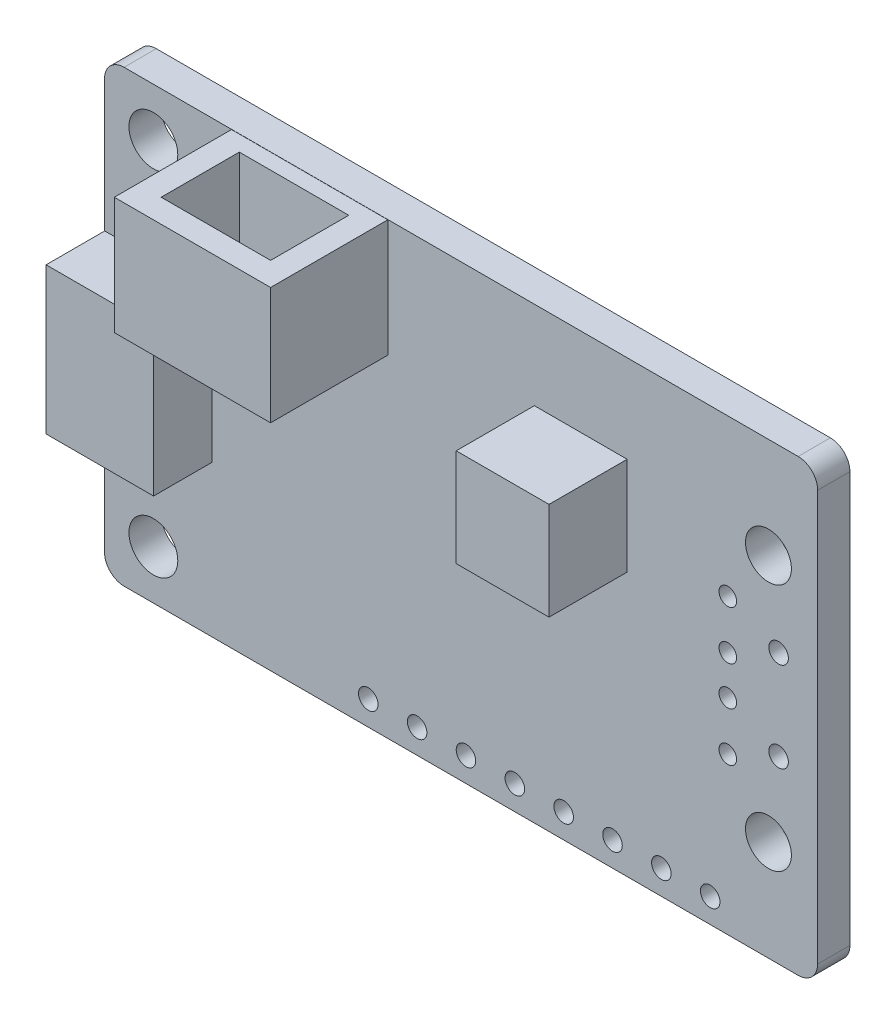
SolidWorks part; units mm, degrees
ref_plane "Front Plane" through (0, 0, 0) normal (0, 0, 1) x (1, 0, 0)
ref_plane "Top Plane" through (0, 0, 0) normal (0, 1, 0) x (1, 0, 0)
ref_plane "Right Plane" through (0, 0, 0) normal (1, 0, 0) x (0, 0, -1)
sketch "Sketch1" plane through (0, 0, 0) normal (0, 0, 1) x (1, 0, 0)
  line L1 (-17.25, -11.5) -> (17.25, -11.5)
  line L2 (-18.25, -10.5) -> (-18.25, 10.5)
  line L3 (-17.25, 11.5) -> (17.25, 11.5)
  line L4 (18.25, -10.5) -> (18.25, 10.5)
  line L5 (-18.25, -11.5) -> (18.25, 11.5) construction
  line L6 (-18.25, 11.5) -> (18.25, -11.5) construction
  arc A0 (-17.25, -11.5) -> (-18.25, -10.5) centre (-17.25, -10.5) cw
  arc A1 (17.25, -11.5) -> (18.25, -10.5) centre (17.25, -10.5) ccw
  arc A2 (17.25, 11.5) -> (18.25, 10.5) centre (17.25, 10.5) cw
  arc A3 (-18.25, 10.5) -> (-17.25, 11.5) centre (-17.25, 10.5) cw
  point P0 (0, 0)
  dimension "D3" = 1
  dimension "D1" = 36.5
  dimension "D2" = 23
extrude "Base" add sketch "Sketch1" along normal blind 1.65
sketch "Sketch2" plane through (0, 0, 1.65) normal (0, 0, 1) x (1, 0, 0)
  line L0 (17.25, 11.5) -> (-17.25, 11.5) construction
  line L1 (-18.25, 10.5) -> (-18.25, -10.5) construction
  circle A0 centre (-15.75, 9) radius 1.25
  dimension "D1" = 2.5
  dimension "D2" = 2.5
  dimension "D3" = 2.5
extrude "Cut-Extrude1" cut sketch "Sketch2" against normal through all
mirror "Mirror1" about plane through (0, 0, 0) normal (0, 1, 0) of "Cut-Extrude1"
sketch "Sketch3" plane through (0, 0, 1.65) normal (0, 0, 1) x (1, 0, 0)
  line L0 (-17.25, -11.5) -> (17.25, -11.5) construction
  line L1 (18.25, -10.5) -> (18.25, 10.5) construction
  circle A0 centre (12.75, -10.25) radius 0.5
  dimension "D1" = 1
  dimension "D2" = 1.25
  dimension "D3" = 5.5
extrude "Cut-Extrude2" cut sketch "Sketch3" against normal through all
pattern_linear "LPattern1" count 8 spacing 2.5 along (-1, 0, 0) of "Cut-Extrude2"
sketch "Sketch4" plane through (0, 0, 1.65) normal (0, 0, 1) x (1, 0, 0)
  line L0 (-17.25, -11.5) -> (17.25, -11.5) construction
  circle A1 centre (15.7309, -6.3475) radius 1.175
  dimension "D1" = 2.35
  dimension "D3" = 5.1525
extrude "Cut-Extrude3" cut sketch "Sketch4" against normal through all
sketch "Sketch9" plane through (0, 0, 1.65) normal (0, 0, 1) x (1, 0, 0)
  line L0 (18.25, -10.5) -> (18.25, 10.5) construction
  line L1 (17.25, 11.5) -> (-17.25, 11.5) construction
  circle A0 centre (13.65, 1) radius 0.45
  circle A1 centre (13.65, 3.5) radius 0.45
  dimension "D1" = 0.9
  dimension "D2" = 0.9
  dimension "D3" = 4.6
  dimension "D4" = 8
  dimension "D5" = 10.5
extrude "Cut-Extrude6" cut sketch "Sketch9" against normal through all
sketch "Sketch10" plane through (0, 0, 1.65) normal (0, 0, 1) x (1, 0, 0)
  line L0 (18.25, -10.5) -> (18.25, 10.5) construction
  line L1 (17.25, 11.5) -> (-17.25, 11.5) construction
  circle A0 centre (16.25, 2.3) radius 0.5
  dimension "D1" = 1
  dimension "D2" = 2
  dimension "D3" = 9.2
extrude "Cut-Extrude7" cut sketch "Sketch10" against normal through all
mirror "Mirror2" about plane through (0, 0, 0) normal (0, 1, 0) of "Cut-Extrude3"
mirror "Mirror3" about plane through (0, 0, 0) normal (0, 1, 0) of "Cut-Extrude6"
mirror "Mirror4" about plane through (0, 0, 0) normal (0, 1, 0) of "Cut-Extrude7"
sketch "Sketch5" plane through (0, 0, 1.65) normal (0, 0, 1) x (1, 0, 0)
  line L1 (-11.75, 11.49) -> (-3.75, 11.49)
  line L2 (-11.75, 11.49) -> (-11.75, 5.49)
  line L3 (-11.75, 5.49) -> (-3.75, 5.49)
  line L4 (-3.75, 11.49) -> (-3.75, 5.49)
  line L5 (-18.25, 10.5) -> (-18.25, -10.5) construction
  line L7 (17.25, 11.5) -> (-17.25, 11.5) construction
  point P8 (-11.75, 11.5)
  dimension "D1" = 8
  dimension "D2" = 6
  dimension "D3" = 14.5
  dimension "D4" = 0.01
extrude "Boss-Extrude2" add sketch "Sketch5" along normal blind 6
sketch "Sketch6" plane through (0, 11.5, 0) normal (0, 1, 0) x (1, 0, 0)
  line L0 (17.25, 0) -> (-17.25, 0) construction
  line L1 (-10.55, -6.45) -> (-4.95, -6.45)
  line L2 (-10.55, -6.45) -> (-10.55, -2.45)
  line L3 (-10.55, -2.45) -> (-4.95, -2.45)
  line L4 (-4.95, -6.45) -> (-4.95, -2.45)
  line L6 (-3.75, -7.65) -> (-3.75, -1.65) construction
  line L7 (-11.75, -7.65) -> (-11.75, -1.65) construction
  line L9 (-3.75, -7.65) -> (-11.75, -7.65) construction
  dimension "D1" = 2.45
  dimension "D2" = 1.2
  dimension "D3" = 1.2
  dimension "D4" = 1.2
extrude "Cut-Extrude4" cut sketch "Sketch6" against normal blind 4.8
sketch "Sketch7" plane through (0, 0, 1.65) normal (0, 0, 1) x (1, 0, 0)
  line L1 (-18.24, 3.75) -> (-12.74, 3.75)
  line L2 (-18.24, 3.75) -> (-18.24, -3.75)
  line L3 (-18.24, -3.75) -> (-12.74, -3.75)
  line L4 (-12.74, 3.75) -> (-12.74, -3.75)
  line L5 (-18.25, 10.5) -> (-18.25, -10.5) construction
  point P4 (-18.24, 0)
  point P7 (-18.25, 0)
  dimension "D1" = 7.5
  dimension "D2" = 5.5
  dimension "D3" = 0.01
extrude "Boss-Extrude3" add sketch "Sketch7" along normal blind 3
sketch "Sketch8" plane through (-18.24, 0, 0) normal (-1, 0, 0) x (0, 0, 1)
  line L0 (4.65, 3.75) -> (4.65, -3.75) construction
  line L1 (2.15, 3.25) -> (4.15, 3.25)
  line L2 (2.15, 3.25) -> (2.15, -3.25)
  line L3 (2.15, -3.25) -> (4.15, -3.25)
  line L4 (4.15, 3.25) -> (4.15, -3.25)
  line L5 (1.65, 10.5) -> (1.65, -10.5) construction
  line L6 (4.65, 3.75) -> (1.65, 3.75) construction
  line L7 (4.65, -3.75) -> (1.65, -3.75) construction
  dimension "D1" = 0.5
  dimension "D2" = 0.5
  dimension "D3" = 0.5
  dimension "D4" = 0.5
extrude "Cut-Extrude5" cut sketch "Sketch8" against normal blind 5
sketch "Sketch11" plane through (0, 0, 1.65) normal (0, 0, 1) x (1, 0, 0)
  line L0 (18.25, -10.5) -> (18.25, 10.5) construction
  line L1 (3.75, 7) -> (8.5, 7)
  line L2 (3.75, 7) -> (3.75, 2)
  line L3 (3.75, 2) -> (8.5, 2)
  line L4 (8.5, 7) -> (8.5, 2)
  line L5 (17.25, 11.5) -> (-17.25, 11.5) construction
  dimension "D1" = 4.75
  dimension "D2" = 5
  dimension "D3" = 14.5
  dimension "D4" = 9.5
extrude "Boss-Extrude4" add sketch "Sketch11" along normal blind 4
